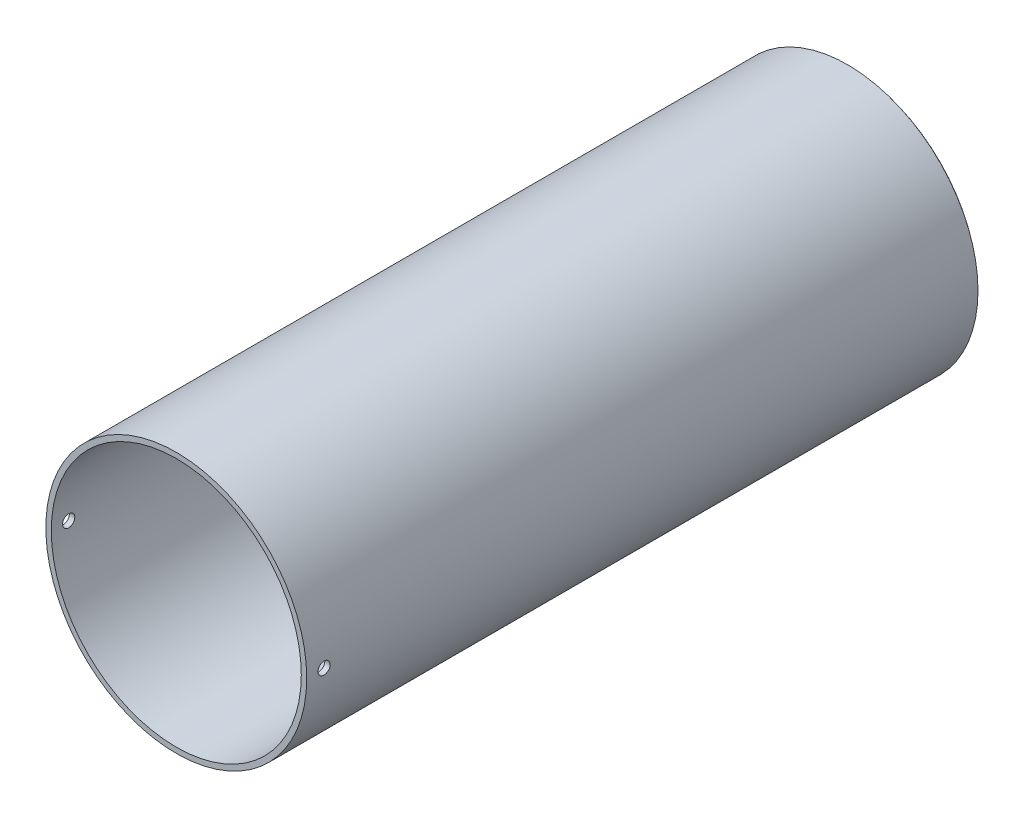
SolidWorks part; units mm, degrees
ref_plane "Front Plane" through (0, 0, 0) normal (0, 0, 1) x (1, 0, 0)
ref_plane "Top Plane" through (0, 0, 0) normal (0, 1, 0) x (1, 0, 0)
ref_plane "Right Plane" through (0, 0, 0) normal (1, 0, 0) x (0, 0, -1)
sketch "Sketch1" plane through (0, 0, 0) normal (1, 0, 0) x (0, 0, -1)
  line L0 (-6.9837, 0) -> (206.4991, 0) construction
  line L1 (0, 36.5125) -> (196.85, 36.5125)
  line L2 (196.85, 36.5125) -> (196.85, 37.084)
  line L3 (196.0704, 38.1) -> (0, 38.1)
  line L4 (0, 38.1) -> (0, 36.5125)
  line L5 (196.0704, 38.1) -> (196.85, 37.084)
  dimension "D1" = 76.2
  dimension "D2" = 196.85
  dimension "D3" = 73.025
  dimension "D4" = 52.5
  dimension "D5" = 1.016
revolve "Revolve1" add sketch "Sketch1" angle 360 about L0
sketch "Sketch2" plane through (0, 0, 0) normal (1, 0, 0) x (0, 0, -1)
  line L0 (0, 38.1) -> (0, -38.1) construction
  circle A0 centre (5.08, 0) radius 1.778
  dimension "D1" = 5.08
  dimension "D2" = 3.556
extrude "Cut-Extrude1" cut sketch "Sketch2" against normal through all both and the other way through all
